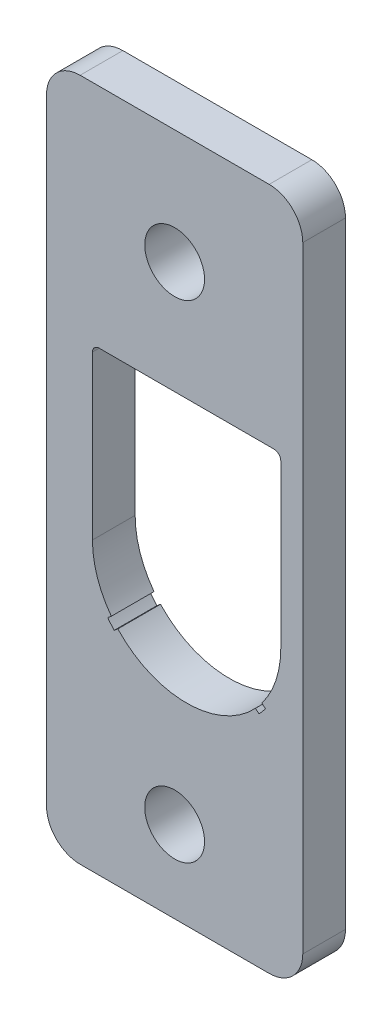
SolidWorks part; units mm, degrees
ref_plane "Front Plane" through (0, 0, 0) normal (0, 0, 1) x (1, 0, 0)
ref_plane "Top Plane" through (0, 0, 0) normal (0, 1, 0) x (1, 0, 0)
ref_plane "Right Plane" through (0, 0, 0) normal (1, 0, 0) x (0, 0, -1)
sketch "Sketch1" plane through (0, 0, 0) normal (0, 0, 1) x (1, 0, 0)
  line L0 (-12.222, -110.928) -> (-12.222, -135.128)
  line L1 (-9.4133, -143.5396) -> (-9.9503, -143.9901)
  line L2 (-8.4491, -144.6886) -> (-8.9861, -145.1392)
  line L3 (12.0051, -144.6886) -> (12.5421, -145.1392)
  line L4 (12.9693, -143.5396) -> (13.5063, -143.9901)
  line L5 (15.778, -135.128) -> (15.778, -110.928)
  line L6 (14.778, -109.928) -> (-11.222, -109.928)
  line L7 (-11.222, -107.928) -> (-10.122, -107.928)
  line L8 (13.678, -107.928) -> (14.778, -107.928)
  line L16 (19.05, -177.8) -> (-19.05, -177.8)
  line L17 (19.05, -76.2) -> (-19.05, -76.2)
  line L18 (19.05, -177.8) -> (19.05, -76.2)
  line L21 (19.05, -177.8) -> (19.05, 177.8) construction
  line L22 (19.05, -177.8) -> (19.05, 177.8) construction
  line L23 (-19.05, -177.8) -> (-19.05, 177.8) construction
  line L24 (-19.05, -177.8) -> (-19.05, 177.8) construction
  line L25 (-19.05, -177.8) -> (-19.05, -76.2)
  line L26 (-19.05, -177.8) -> (-19.05, -76.2)
  line L33 (-11.222, -108.428) -> (-10.122, -108.428)
  line L35 (13.678, -108.428) -> (14.778, -108.428)
  arc A0 (-12.222, -135.128) -> (-9.4133, -143.5396) centre (1.778, -135.128) ccw
  arc A1 (-9.9503, -143.9901) -> (-8.9861, -145.1392) centre (1.778, -135.128) ccw
  arc A2 (-8.4491, -144.6886) -> (12.0051, -144.6886) centre (1.778, -135.128) ccw
  arc A3 (12.5421, -145.1392) -> (13.5063, -143.9901) centre (1.778, -135.128) ccw
  arc A4 (12.9693, -143.5396) -> (15.778, -135.128) centre (1.778, -135.128) ccw
  arc A5 (15.778, -110.928) -> (14.778, -109.928) centre (14.778, -110.928) ccw
  arc A6 (-11.222, -109.928) -> (-12.222, -110.928) centre (-11.222, -110.928) ccw
  dimension "D1" = 101.6
  dimension "D2" = 0.5
extrude "Boss-Extrude1" add sketch "Sketch1" along normal blind 6.35
fillet "Fillet1" radius 5 1 edges at (-19.05, -76.2, 3.175)
fillet "Fillet2" radius 5 1 edges at (19.05, -76.2, 3.175)
fillet "Fillet3" radius 5 1 edges at (19.05, -177.8, 3.175)
fillet "Fillet4" radius 5 1 edges at (-19.05, -177.8, 3.175)
sketch "Sketch2" plane through (0, 0, 6.35) normal (0, 0, 1) x (1, 0, 0)
  line L0 (0, -76.2) -> (0, -177.8) construction
  line L1 (14.05, -76.2) -> (-14.05, -76.2) construction
  line L2 (14.05, -177.8) -> (-14.05, -177.8) construction
  circle A0 centre (0, -93.2344) radius 4.445
  circle A1 centre (0, -165.6437) radius 4.445
  dimension "D1" = 8.89
extrude "Cut-Extrude1" cut sketch "Sketch2" against normal up to next
